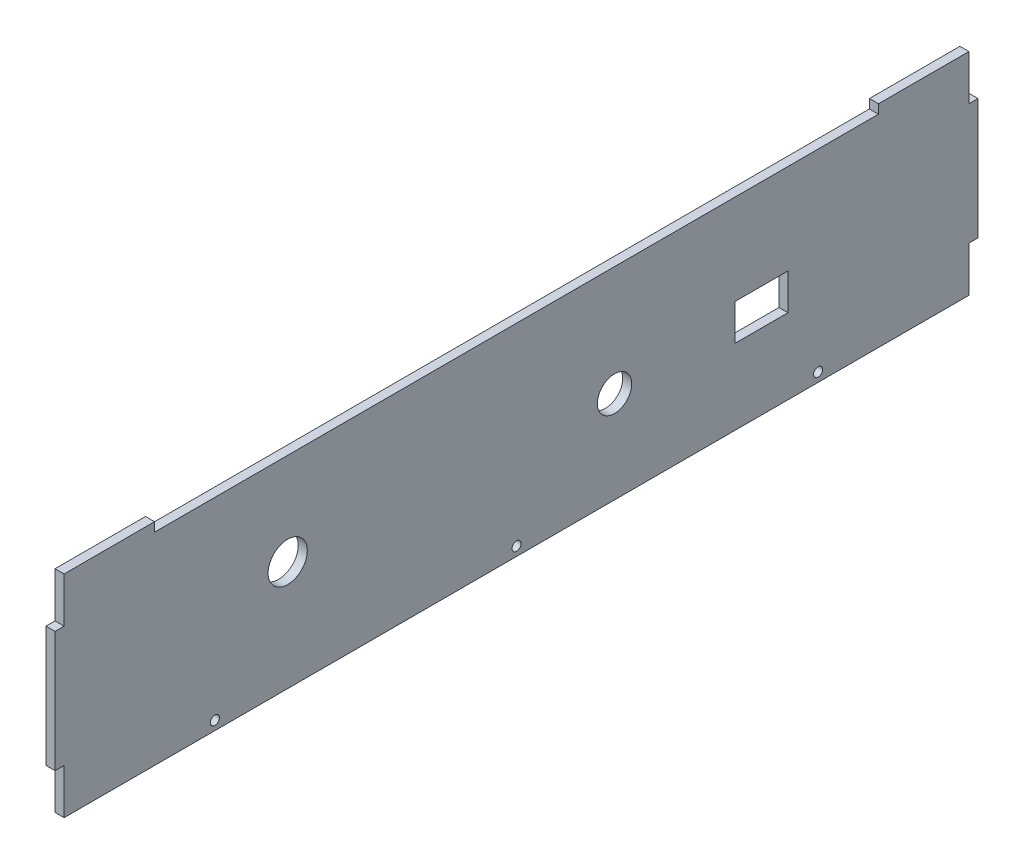
SolidWorks part; units mm, degrees
ref_plane "Front Plane" through (0, 0, 0) normal (0, 0, 1) x (1, 0, 0)
ref_plane "Top Plane" through (0, 0, 0) normal (0, 1, 0) x (1, 0, 0)
ref_plane "Right Plane" through (0, 0, 0) normal (1, 0, 0) x (0, 0, -1)
sketch "Sketch1" plane through (0, 0, 0) normal (1, 0, 0) x (0, 0, -1)
  line L0 (18.8554, 70) -> (318.8554, 70)
  line L1 (318.8554, 70) -> (318.8554, 55)
  line L2 (318.8554, 55) -> (321.8554, 55)
  line L3 (321.8554, 55) -> (321.8554, 15)
  line L4 (321.8554, 15) -> (318.8554, 15)
  line L5 (318.8554, 15) -> (318.8554, 0)
  line L6 (318.8554, 0) -> (18.8554, 0)
  line L7 (18.8554, 0) -> (18.8554, 15)
  line L8 (18.8554, 15) -> (15.8554, 15)
  line L9 (15.8554, 15) -> (15.8554, 55)
  line L10 (15.8554, 55) -> (18.8554, 55)
  line L11 (18.8554, 55) -> (18.8554, 70)
  dimension "D1" = 300
  dimension "D2" = 300
  dimension "D3" = 40
  dimension "D4" = 40
  dimension "D5" = 15
  dimension "D6" = 15
  dimension "D7" = 15
  dimension "D8" = 15
  dimension "D9" = 3
  dimension "D10" = 3
  dimension "D11" = 3
  dimension "D12" = 3
extrude "Boss-Extrude2" add sketch "Sketch1" along normal blind 3
sketch "Sketch3" plane through (3, 0, 0) normal (1, 0, 0) x (0, 0, -1)
  line L0 (48.8554, 70) -> (48.8554, 67)
  line L1 (318.8554, 70) -> (18.8554, 70) construction
  line L2 (48.8554, 67) -> (288.8554, 67)
  line L3 (288.8554, 67) -> (288.8554, 70)
  line L4 (318.8554, 55) -> (318.8554, 70) construction
  dimension "D1" = 240
  dimension "D2" = 3
  dimension "D3" = 30
extrude "Cut-Extrude1" cut sketch "Sketch3" against normal blind 3 and the other way through all
sketch "Sketch4" plane through (3, 0, 0) normal (1, 0, 0) x (0, 0, -1)
  line L0 (318.8554, 0) -> (318.8554, 15) construction
  line L1 (241.3554, 37) -> (258.8554, 37)
  line L2 (241.3554, 37) -> (241.3554, 25)
  line L3 (241.3554, 25) -> (258.8554, 25)
  line L4 (258.8554, 37) -> (258.8554, 25)
  line L5 (18.8554, 0) -> (318.8554, 0) construction
  dimension "D1" = 17.5
  dimension "D2" = 12
  dimension "D3" = 60
  dimension "D4" = 25
extrude "Cut-Extrude2" cut sketch "Sketch4" against normal blind 10
sketch "Sketch5" plane through (3, 0, 0) normal (1, 0, 0) x (0, 0, -1)
  line L0 (241.3554, 37) -> (241.3554, 25) construction
  line L1 (18.8554, 0) -> (318.8554, 0) construction
  circle A0 centre (201.3554, 30.5) radius 5.7
  dimension "D1" = 11.4
  dimension "D2" = 40
  dimension "D3" = 30.5
extrude "Cut-Extrude3" cut sketch "Sketch5" against normal blind 10
sketch "Sketch6" plane through (3, 0, 0) normal (1, 0, 0) x (0, 0, -1)
  circle A0 centre (92.9906, 36.3822) radius 6.5
  dimension "D1" = 13
extrude "Cut-Extrude4" cut sketch "Sketch6" against normal blind 10
sketch "Sketch7" plane through (3, 0, 0) normal (1, 0, 0) x (0, 0, -1)
  line L0 (18.8554, 0) -> (318.8554, 0) construction
  line L1 (318.8554, 0) -> (318.8554, 15) construction
  circle A0 centre (268.8554, 3) radius 1.5
  circle A1 centre (168.8554, 3) radius 1.5
  circle A2 centre (68.8554, 3) radius 1.5
  dimension "D1" = 3
  dimension "D2" = 3
  dimension "D3" = 50
  dimension "D4" = 3
extrude "Cut-Extrude5" cut sketch "Sketch7" against normal blind 10
